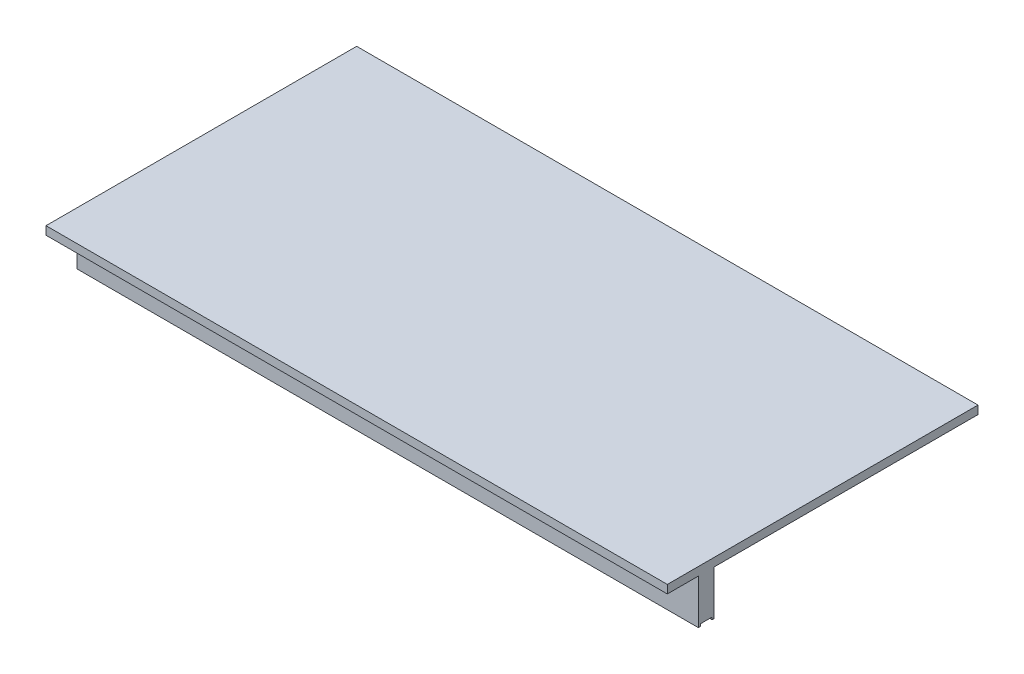
SolidWorks part; units mm, degrees
ref_plane "Front Plane" through (0, 0, 0) normal (0, 0, 1) x (1, 0, 0)
ref_plane "Top Plane" through (0, 0, 0) normal (0, 1, 0) x (1, 0, 0)
ref_plane "Right Plane" through (0, 0, 0) normal (1, 0, 0) x (0, 0, -1)
sketch "Sketch1" plane through (0, 0, 0) normal (1, 0, 0) x (0, 0, -1)
  line L1 (0, 0) -> (500, 0)
  line L2 (0, 0) -> (0, 13.338)
  line L3 (0, 13.338) -> (500, 13.338)
  line L4 (500, 0) -> (500, 13.338)
  line L5 (50, 0) -> (53, 0)
  line L6 (50, 0) -> (50, -72)
  line L7 (50, -72) -> (53, -72)
  line L8 (53, 0) -> (53, -72)
  line L9 (53, -68.2291) -> (72, -68.2291)
  line L10 (53, -68.2291) -> (53, 0)
  line L11 (53, 0) -> (72, 0)
  line L12 (72, -68.2291) -> (72, 0)
  line L13 (72, 0) -> (75, 0)
  line L14 (72, 0) -> (72, -72)
  line L15 (72, -72) -> (75, -72)
  line L16 (75, 0) -> (75, -72)
  dimension "D1" = 25
  dimension "D2" = 72
  dimension "D3" = 500
  dimension "D4" = 3
  dimension "D5" = 3
  dimension "D6" = 50
extrude "Boss-Extrude1" add sketch "Sketch1" along normal blind 1000 contours L1 L4 L3 L2 | L9 L12 L1 L8 | L13 L16 L15 L14
